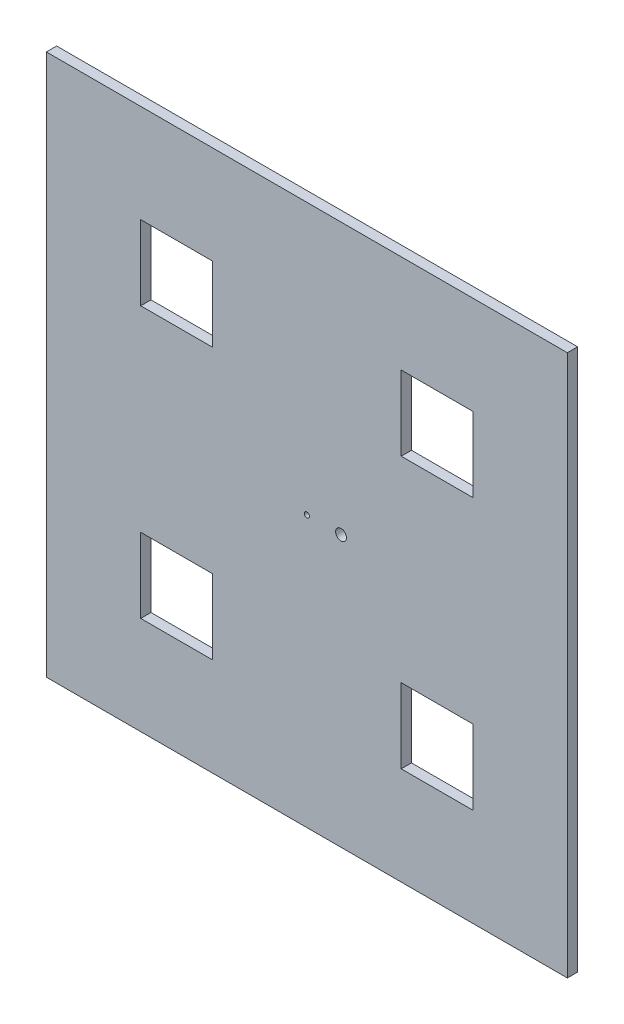
SolidWorks part; units mm, degrees
material "Acrylic (Medium-high impact)"
ref_plane "Front Plane" through (0, 0, 0) normal (0, 0, 1) x (1, 0, 0)
ref_plane "Top Plane" through (0, 0, 0) normal (0, 1, 0) x (1, 0, 0)
ref_plane "Right Plane" through (0, 0, 0) normal (1, 0, 0) x (0, 0, -1)
sketch "Sketch1" plane through (0, 0, 0) normal (0, 0, 1) x (1, 0, 0)
  line L1 (152.4, -158.4) -> (-152.4, -158.4)
  line L2 (152.4, -158.4) -> (152.4, 158.4)
  line L3 (152.4, 158.4) -> (-152.4, 158.4)
  line L4 (-152.4, -158.4) -> (-152.4, 158.4)
  line L5 (152.4, -158.4) -> (-152.4, 158.4) construction
  line L6 (152.4, 158.4) -> (-152.4, -158.4) construction
  point P0 (0, 0)
  dimension "D1" = 316.8
  dimension "D2" = 304.8
extrude "Boss-Extrude1" add sketch "Sketch1" along normal blind 6
sketch "Sketch3" plane through (0, 0, 6) normal (0, 0, 1) x (1, 0, 0)
  line L0 (-152.4, 0) -> (0, 158.4) construction
  line L1 (-152.4, 158.4) -> (-152.4, -158.4) construction
  line L2 (152.4, 158.4) -> (-152.4, 158.4) construction
  line L3 (0, 158.4) -> (152.4, 0) construction
  line L4 (152.4, -158.4) -> (152.4, 158.4) construction
  line L5 (152.4, 0) -> (0, -158.4) construction
  line L6 (-152.4, -158.4) -> (152.4, -158.4) construction
  line L7 (0, -158.4) -> (-152.4, 0) construction
  line L9 (-55.2, 57.3732) -> (-97.2, 57.3732)
  line L10 (-55.2, 57.3732) -> (-55.2, 101.0268)
  line L11 (-55.2, 101.0268) -> (-97.2, 101.0268)
  line L12 (-97.2, 57.3732) -> (-97.2, 101.0268)
  line L13 (-55.2, 57.3732) -> (-97.2, 101.0268) construction
  line L14 (-55.2, 101.0268) -> (-97.2, 57.3732) construction
  line L15 (97.2, 57.3732) -> (55.2, 57.3732)
  line L16 (97.2, 57.3732) -> (97.2, 101.0268)
  line L17 (97.2, 101.0268) -> (55.2, 101.0268)
  line L18 (55.2, 57.3732) -> (55.2, 101.0268)
  line L19 (97.2, 57.3732) -> (55.2, 101.0268) construction
  line L20 (97.2, 101.0268) -> (55.2, 57.3732) construction
  line L21 (97.2, -101.0268) -> (55.2, -101.0268)
  line L22 (97.2, -101.0268) -> (97.2, -57.3732)
  line L23 (97.2, -57.3732) -> (55.2, -57.3732)
  line L24 (55.2, -101.0268) -> (55.2, -57.3732)
  line L25 (97.2, -101.0268) -> (55.2, -57.3732) construction
  line L26 (97.2, -57.3732) -> (55.2, -101.0268) construction
  line L27 (-55.2, -101.0268) -> (-97.2, -101.0268)
  line L28 (-55.2, -101.0268) -> (-55.2, -57.3732)
  line L29 (-55.2, -57.3732) -> (-97.2, -57.3732)
  line L30 (-97.2, -101.0268) -> (-97.2, -57.3732)
  line L31 (-55.2, -101.0268) -> (-97.2, -57.3732) construction
  line L32 (-55.2, -57.3732) -> (-97.2, -101.0268) construction
  point P6 (-76.2, 79.2)
  point P17 (76.2, 79.2)
  point P22 (76.2, -79.2)
  point P27 (-76.2, -79.2)
  dimension "D1" = 42
  dimension "D2" = 42
  dimension "D3" = 42
  dimension "D4" = 42
extrude "Cut-Extrude2" cut sketch "Sketch3" against normal through all
sketch "Sketch4" plane through (0, 0, 6) normal (0, 0, 1) x (1, 0, 0)
  line L0 (-152.4, -158.4) -> (152.4, 158.4) construction
  circle A0 centre (0, 0) radius 1.5
  dimension "D1" = 3
extrude "Cut-Extrude3" cut sketch "Sketch4" against normal through all
sketch "Sketch5" plane through (0, 0, 6) normal (0, 0, 1) x (1, 0, 0)
  circle A0 centre (20, 0) radius 3.175
  dimension "D1" = 6.35
  dimension "D2" = 20
extrude "Cut-Extrude4" cut sketch "Sketch5" against normal through all
